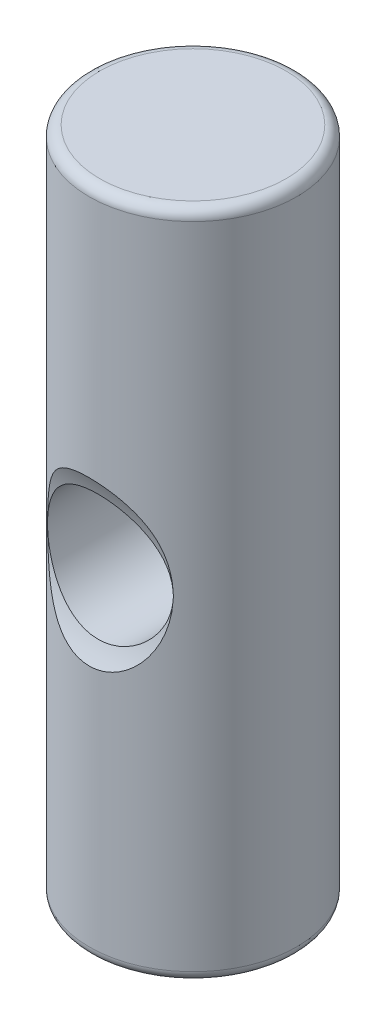
SolidWorks part; units mm, degrees
material "AISI 1045 Steel, cold drawn"
ref_plane "Front Plane" through (0, 0, 0) normal (0, 0, 1) x (1, 0, 0)
ref_plane "Top Plane" through (0, 0, 0) normal (0, 1, 0) x (1, 0, 0)
ref_plane "Right Plane" through (0, 0, 0) normal (1, 0, 0) x (0, 0, -1)
sketch "Sketch1" plane through (0, 0, 0) normal (0, 1, 0) x (1, 0, 0)
  circle A0 centre (0, 0) radius 2.475
  dimension "D1" = 4.95
extrude "Boss-Extrude1" add sketch "Sketch1" along normal mid plane 16
sketch "Sketch2" plane through (0, 0, 0) normal (0, 0, 1) x (1, 0, 0)
  circle A0 centre (0, 0) radius 1.5
  dimension "D1" = 3
extrude "Cut-Extrude1" cut sketch "Sketch2" against normal through all both and the other way through all
sketch "Sketch5" plane through (0, 0, 0) normal (1, 0, 0) x (0, 0, -1)
  circle A0 centre (-5.97, 0) radius 4
  dimension "D1" = 8
  dimension "D2" = 5.97
extrude "Cut-Extrude3" cut sketch "Sketch5" against normal through all both and the other way through all
fillet "Fillet1" radius 0.25 2 edges at (0, -8, 2.475) (0, 8, 2.475)
